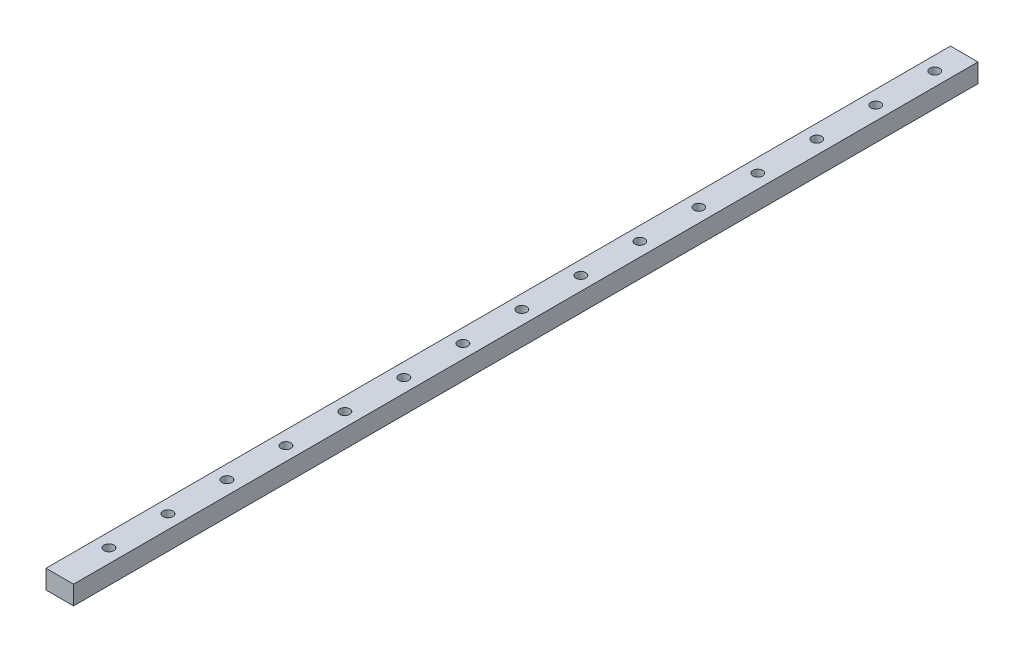
SolidWorks part; units mm, degrees
ref_plane "前视基准面" through (0, 0, 0) normal (0, 0, 1) x (1, 0, 0)
ref_plane "上视基准面" through (0, 0, 0) normal (0, 1, 0) x (1, 0, 0)
ref_plane "右视基准面" through (0, 0, 0) normal (1, 0, 0) x (0, 0, -1)
sketch "草图1" plane through (0, 0, 0) normal (0, 1, 0) x (1, 0, 0)
  line L1 (-3.5, 115) -> (3.5, 115)
  line L2 (-3.5, 115) -> (-3.5, -115)
  line L3 (-3.5, -115) -> (3.5, -115)
  line L4 (3.5, 115) -> (3.5, -115)
  line L5 (-3.5, 115) -> (3.5, -115) construction
  line L6 (-3.5, -115) -> (3.5, 115) construction
  circle A0 centre (0, 107.5) radius 1.25
  circle A1 centre (0, 92.5) radius 1.25
  circle A2 centre (0, 77.5) radius 1.25
  circle A3 centre (0, 62.5) radius 1.25
  circle A4 centre (0, 47.5) radius 1.25
  circle A5 centre (0, 32.5) radius 1.25
  circle A6 centre (0, 17.5) radius 1.25
  circle A7 centre (0, 2.5) radius 1.25
  circle A8 centre (0, -12.5) radius 1.25
  circle A9 centre (0, -27.5) radius 1.25
  circle A10 centre (0, -42.5) radius 1.25
  circle A11 centre (0, -57.5) radius 1.25
  circle A12 centre (0, -72.5) radius 1.25
  circle A13 centre (0, -87.5) radius 1.25
  circle A14 centre (0, -102.5) radius 1.25
  point P0 (0, 0)
  dimension "D3" = 2.5
  dimension "D1" = 230
  dimension "D2" = 7
  dimension "D4" = 7.5
  dimension "D5" = 15
extrude "凸台-拉伸1" add sketch "草图1" along normal blind 4.8
